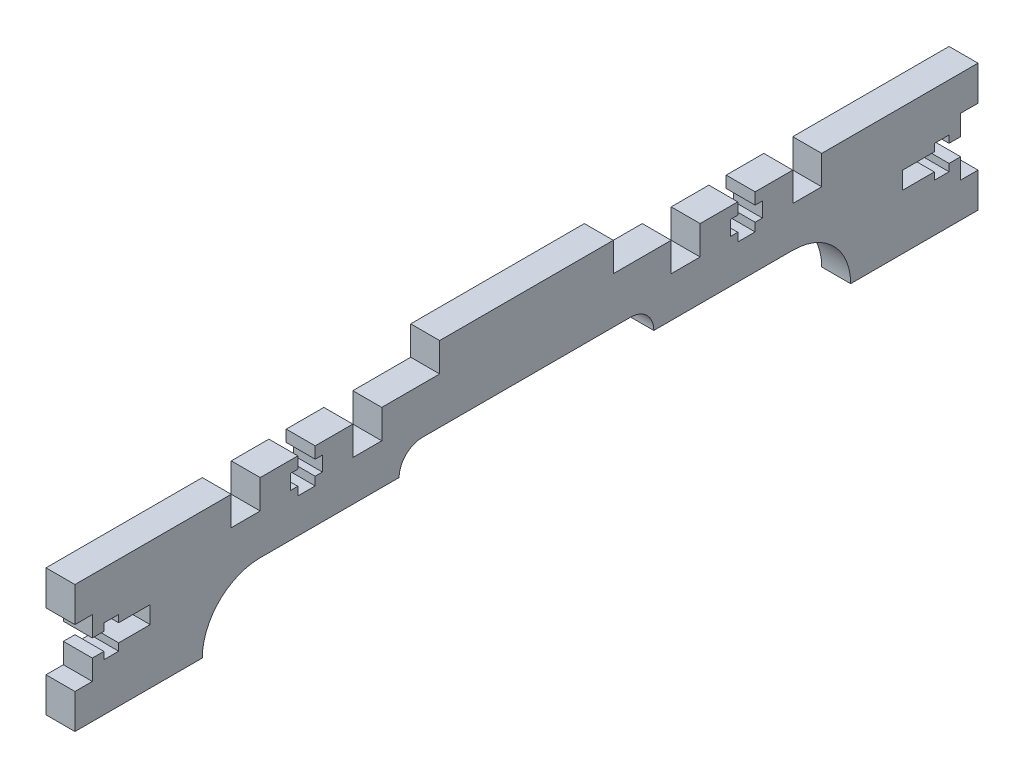
SolidWorks part; units mm, degrees
ref_plane "Front Plane" through (0, 0, 0) normal (0, 0, 1) x (1, 0, 0)
ref_plane "Top Plane" through (0, 0, 0) normal (0, 1, 0) x (1, 0, 0)
ref_plane "Right Plane" through (0, 0, 0) normal (1, 0, 0) x (0, 0, -1)
sketch "Sketch1" plane through (0, 0, 0) normal (0, 0, 1) x (1, 0, 0)
  line L0 (31.394, 59.5854) -> (31.394, 39.9745) construction
  line L1 (32.894, 57.0854) -> (38.394, 57.0854) construction
  line L2 (28.894, 35.0854) -> (33.894, 35.0854)
  line L3 (28.894, 35.0854) -> (28.894, 57.0854)
  line L4 (28.894, 57.0854) -> (33.894, 57.0854)
  line L5 (33.894, 35.0854) -> (33.894, 57.0854)
  line L6 (28.894, 35.0854) -> (33.894, 57.0854) construction
  line L7 (28.894, 57.0854) -> (33.894, 35.0854) construction
  point P3 (31.394, 46.0854)
  dimension "D1" = 5
  dimension "D2" = 22
extrude "Boss-Extrude1" add sketch "Sketch1" along normal blind 150
sketch "Sketch2" plane through (33.894, 0, 0) normal (1, 0, 0) x (0, 0, -1)
  line L0 (-75, 57.0854) -> (-75, 29.1011) construction
  line L1 (-150, 57.0854) -> (0, 57.0854) construction
  line L2 (-93, 49.0854) -> (-57, 49.0854)
  line L3 (-53, 45.0854) -> (-29, 45.0854)
  line L4 (-150, 35.0854) -> (0, 35.0854) construction
  line L5 (-131, 35.0854) -> (-19, 35.0854)
  line L6 (-53, 45.0854) -> (-60.4269, 45.0854) construction
  line L7 (-53, 45.0854) -> (-53, -34.1741) construction
  line L8 (-57, 53.0854) -> (-57, 49.0854) construction
  line L9 (-97, 45.0854) -> (-121, 45.0854)
  arc A0 (-57, 49.0854) -> (-53, 45.0854) centre (-57, 45.0854) cw
  arc A1 (-29, 45.0854) -> (-19, 35.0854) centre (-29, 35.0854) cw
  arc A2 (-121, 45.0854) -> (-131, 35.0854) centre (-121, 35.0854) ccw
  arc A3 (-93, 49.0854) -> (-97, 45.0854) centre (-93, 45.0854) ccw
  point P13 (-75, 49.0854)
  point P25 (-75, 35.0854)
  dimension "D1" = 8
  dimension "D2" = 12
  dimension "D3" = 56
extrude "Cut-Extrude1" cut sketch "Sketch2" against normal through all
sketch "Sketch3" plane through (33.894, 0, 0) normal (1, 0, 0) x (0, 0, -1)
  line L0 (-38.5, 57.0854) -> (-38.5, 55.0854) construction
  line L1 (-38.5, 51.0854) -> (-35.5, 51.0854) construction
  line L2 (-38.5, 52.5354) -> (-38.5, 51.0854) construction
  line L3 (-39.75, 52.5354) -> (-38.5, 52.5354) construction
  line L4 (-35.5, 51.0854) -> (-35.5, 52.5354) construction
  line L5 (-35.5, 52.5354) -> (-34.25, 52.5354) construction
  line L6 (-34.25, 52.5354) -> (-34.25, 55.0854) construction
  line L7 (-34.25, 55.0854) -> (-35.5, 55.0854) construction
  line L8 (-35.5, 55.0854) -> (-35.5, 57.0854) construction
  line L9 (-39.75, 55.0854) -> (-39.75, 52.5354) construction
  line L10 (-38.5, 55.0854) -> (-39.75, 55.0854) construction
  line L11 (-38.5, 51.0854) -> (-35.5, 51.0854)
  line L12 (-38.5, 52.5354) -> (-38.5, 51.0854)
  line L13 (-39.75, 52.5354) -> (-38.5, 52.5354)
  line L14 (-35.5, 51.0854) -> (-35.5, 52.5354)
  line L15 (-35.5, 52.5354) -> (-34.25, 52.5354)
  line L16 (-34.25, 52.5354) -> (-34.25, 55.0854)
  line L17 (-34.25, 55.0854) -> (-35.5, 55.0854)
  line L18 (-35.5, 55.0854) -> (-35.5, 57.0854)
  line L19 (-39.75, 55.0854) -> (-39.75, 52.5354)
  line L20 (-38.5, 57.0854) -> (-38.5, 55.0854)
  line L21 (-38.5, 55.0854) -> (-39.75, 55.0854)
  line L22 (-38.5, 57.0854) -> (-35.5, 57.0854)
  line L23 (-75, 62.0854) -> (-75, 38.7657) construction
  line L24 (-150, 62.0854) -> (0, 62.0854) construction
  line L25 (-111.5, 57.0854) -> (-114.5, 57.0854)
  line L26 (-111.5, 55.0854) -> (-110.25, 55.0854)
  line L27 (-111.5, 57.0854) -> (-111.5, 55.0854)
  line L28 (-110.25, 55.0854) -> (-110.25, 52.5354)
  line L29 (-114.5, 55.0854) -> (-114.5, 57.0854)
  line L30 (-115.75, 55.0854) -> (-114.5, 55.0854)
  line L31 (-115.75, 52.5354) -> (-115.75, 55.0854)
  line L32 (-114.5, 52.5354) -> (-115.75, 52.5354)
  line L33 (-114.5, 51.0854) -> (-114.5, 52.5354)
  line L34 (-110.25, 52.5354) -> (-111.5, 52.5354)
  line L35 (-111.5, 52.5354) -> (-111.5, 51.0854)
  line L36 (-111.5, 51.0854) -> (-114.5, 51.0854)
  line L37 (0, 46.0854) -> (-30.0012, 46.0854) construction
  line L38 (0, 35.0854) -> (0, 57.0854) construction
  line L39 (-50, 46.0854) -> (3, 46.0854) construction
  line L40 (-39.75, 52.5354) -> (-34.25, 52.5354) construction
  line L41 (-10, 44.5854) -> (-4.55, 44.5854)
  line L42 (-10, 44.5854) -> (-10, 47.5854)
  line L43 (-10, 47.5854) -> (-4.55, 47.5854)
  line L44 (0, 44.5854) -> (0, 47.5854)
  line L45 (-10, 44.5854) -> (0, 47.5854) construction
  line L46 (-10, 47.5854) -> (0, 44.5854) construction
  line L47 (-4.55, 43.3354) -> (-2, 43.3354)
  line L48 (-4.55, 43.3354) -> (-4.55, 44.5854)
  line L49 (-4.55, 48.8354) -> (-2, 48.8354)
  line L50 (-2, 43.3354) -> (-2, 44.5854)
  line L51 (-4.55, 43.3354) -> (-2, 48.8354) construction
  line L52 (-4.55, 48.8354) -> (-2, 43.3354) construction
  line L53 (-2, 47.5854) -> (0, 47.5854)
  line L54 (-2, 47.5854) -> (-2, 48.8354)
  line L55 (-2, 44.5854) -> (0, 44.5854)
  line L56 (-4.55, 48.8354) -> (-4.55, 43.3354) construction
  line L57 (-4.55, 47.5854) -> (-4.55, 48.8354)
  line L58 (-145.45, 48.8354) -> (-145.45, 43.3354) construction
  line L59 (-145.45, 48.8354) -> (-148, 43.3354) construction
  line L60 (-145.45, 43.3354) -> (-148, 48.8354) construction
  line L61 (-140, 47.5854) -> (-150, 44.5854) construction
  line L62 (-140, 44.5854) -> (-150, 47.5854) construction
  line L63 (-145.45, 47.5854) -> (-145.45, 48.8354)
  line L64 (-148, 44.5854) -> (-150, 44.5854)
  line L65 (-148, 47.5854) -> (-148, 48.8354)
  line L66 (-148, 47.5854) -> (-150, 47.5854)
  line L67 (-148, 43.3354) -> (-148, 44.5854)
  line L68 (-145.45, 48.8354) -> (-148, 48.8354)
  line L69 (-145.45, 43.3354) -> (-145.45, 44.5854)
  line L70 (-145.45, 43.3354) -> (-148, 43.3354)
  line L71 (-150, 44.5854) -> (-150, 47.5854)
  line L72 (-140, 47.5854) -> (-145.45, 47.5854)
  line L73 (-140, 44.5854) -> (-140, 47.5854)
  line L74 (-140, 44.5854) -> (-145.45, 44.5854)
  point P34 (-5, 46.0854)
  point P39 (-3.275, 46.0854)
  point P60 (-146.725, 46.0854)
  point P61 (-145, 46.0854)
  dimension "D1" = 3
  dimension "D2" = 10
  dimension "D3" = 2
extrude "Cut-Extrude2" cut sketch "Sketch3" against normal through all
sketch "Sketch4" plane through (0, 0, 0) normal (0, 0, -1) x (-1, 0, 0)
  line L0 (-28.894, 44.5854) -> (-28.894, 35.0854) construction
  line L1 (-33.894, 35.0854) -> (-28.894, 35.0854)
  line L2 (-33.894, 35.0854) -> (-33.894, 41.0854)
  line L3 (-33.894, 41.0854) -> (-28.894, 41.0854)
  line L4 (-28.894, 35.0854) -> (-28.894, 41.0854)
  line L5 (-28.894, 57.0854) -> (-28.894, 47.5854) construction
  line L6 (-33.894, 57.0854) -> (-28.894, 57.0854)
  line L7 (-33.894, 57.0854) -> (-33.894, 51.0854)
  line L8 (-33.894, 51.0854) -> (-28.894, 51.0854)
  line L9 (-28.894, 57.0854) -> (-28.894, 51.0854)
  dimension "D1" = 6
  dimension "D2" = 6
extrude "Boss-Extrude2" add sketch "Sketch4" along normal blind 3
sketch "Sketch5" plane through (0, 0, 150) normal (0, 0, 1) x (1, 0, 0)
  line L4 (33.894, 57.0854) -> (28.894, 57.0854)
  line L5 (28.894, 57.0854) -> (28.894, 51.0854)
  line L6 (28.894, 51.0854) -> (33.894, 51.0854)
  line L7 (33.894, 51.0854) -> (33.894, 57.0854)
  line L8 (33.894, 57.0854) -> (28.894, 57.0854)
  line L9 (28.894, 57.0854) -> (28.894, 51.0854)
  line L10 (28.894, 51.0854) -> (33.894, 51.0854)
  line L11 (33.894, 51.0854) -> (33.894, 57.0854)
  line L12 (28.894, 35.0854) -> (33.894, 35.0854)
  line L13 (28.894, 41.0854) -> (28.894, 35.0854)
  line L14 (33.894, 41.0854) -> (28.894, 41.0854)
  line L15 (33.894, 35.0854) -> (33.894, 41.0854)
  line L16 (28.894, 35.0854) -> (33.894, 35.0854)
  line L17 (28.894, 41.0854) -> (28.894, 35.0854)
  line L18 (33.894, 41.0854) -> (28.894, 41.0854)
  line L19 (33.894, 35.0854) -> (33.894, 41.0854)
  dimension "D1" = 0
  dimension "D2" = 0
extrude "Boss-Extrude3" add sketch "Sketch5" along normal blind 3
sketch "Sketch6" plane through (33.894, 0, 0) normal (1, 0, 0) x (0, 0, -1)
  line L0 (-111.5, 57.0854) -> (-38.5, 57.0854) construction
  line L1 (-150, 62.0854) -> (0, 62.0854) construction
  line L2 (-60, 57.0854) -> (-60, 62.0854) construction
  line L3 (-90, 57.0854) -> (-90, 62.0854) construction
  line L4 (-111.5, 57.0854) -> (-38.5, 57.0854)
  line L5 (-150, 62.0854) -> (0, 62.0854)
  line L6 (-60, 57.0854) -> (-60, 62.0854)
  line L7 (-90, 57.0854) -> (-90, 62.0854)
extrude "Boss-Extrude4" add sketch "Sketch6" against normal blind 5 contours L7 L4 L6 L5
sketch "Sketch7" plane through (28.894, 0, 0) normal (-1, 0, 0) x (0, 0, 1)
  line L0 (29, 52.0854) -> (29, 57.0854) construction
  line L1 (24, 57.0854) -> (24, 52.0854) construction
  line L2 (24, 52.0854) -> (29, 52.0854) construction
  line L3 (121, 57.0854) -> (121, 52.0854) construction
  line L4 (121, 52.0854) -> (126, 52.0854) construction
  line L5 (126, 52.0854) -> (126, 57.0854) construction
  line L6 (121, 57.0854) -> (121, 52.0854)
  line L7 (126, 52.0854) -> (126, 57.0854)
  line L8 (121, 52.0854) -> (126, 52.0854)
  line L9 (24, 57.0854) -> (24, 52.0854)
  line L10 (29, 52.0854) -> (29, 57.0854)
  line L11 (24, 52.0854) -> (29, 52.0854)
  line L12 (24, 57.0854) -> (29, 57.0854)
  line L13 (121, 57.0854) -> (126, 57.0854)
extrude "Cut-Extrude3" cut sketch "Sketch7" against normal through all
sketch "Sketch8" plane through (28.894, 0, 0) normal (-1, 0, 0) x (0, 0, 1)
  line L0 (37, 51.0854) -> (37, 29.7055) construction
  line L1 (38.5, 51.0854) -> (35.5, 51.0854) construction
  line L2 (29, 52.0854) -> (29, 57.0854) construction
  line L3 (24, 57.0854) -> (24, 52.0854) construction
  line L4 (24, 52.0854) -> (29, 52.0854) construction
  line L5 (29, 52.0854) -> (29, 57.0854) construction
  line L6 (24, 57.0854) -> (24, 52.0854) construction
  line L7 (24, 52.0854) -> (29, 52.0854) construction
  line L8 (24, 57.0854) -> (29, 57.0854) construction
  line L9 (50, 57.0854) -> (45, 57.0854)
  line L10 (50, 52.0854) -> (45, 52.0854)
  line L11 (50, 57.0854) -> (50, 52.0854)
  line L12 (45, 52.0854) -> (45, 57.0854)
  line L13 (75, 62.0854) -> (75, 16.0923) construction
  line L14 (90, 62.0854) -> (60, 62.0854) construction
  line L15 (105, 52.0854) -> (105, 57.0854)
  line L16 (100, 57.0854) -> (100, 52.0854)
  line L17 (100, 52.0854) -> (105, 52.0854)
  line L18 (100, 57.0854) -> (105, 57.0854)
extrude "Cut-Extrude4" cut sketch "Sketch8" against normal through all
